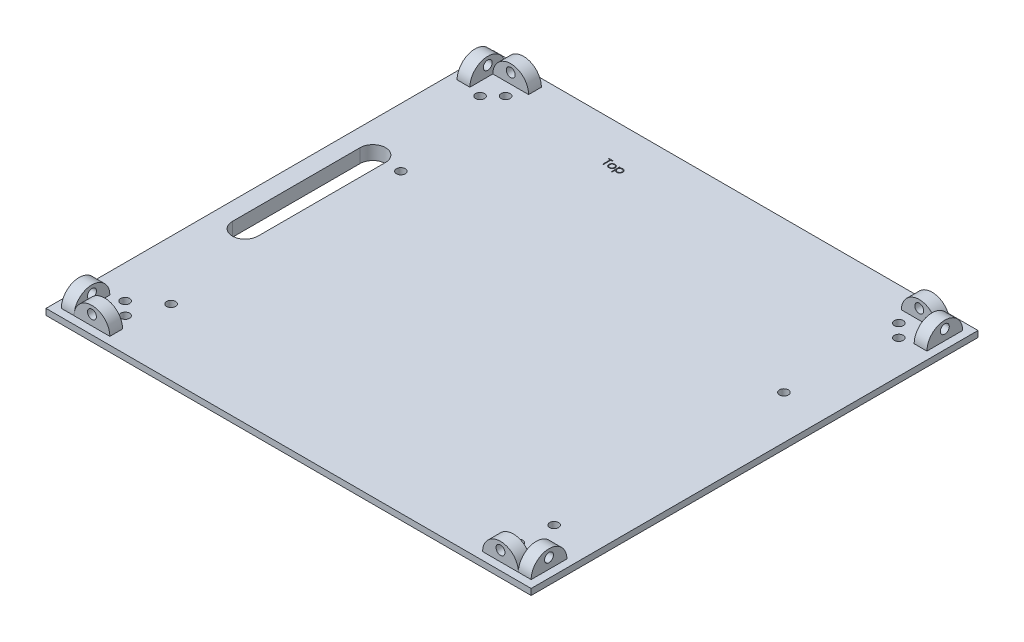
SolidWorks part; units mm, degrees
ref_plane "Front Plane" through (0, 0, 0) normal (0, 0, 1) x (1, 0, 0)
ref_plane "Top Plane" through (0, 0, 0) normal (0, 1, 0) x (1, 0, 0)
ref_plane "Right Plane" through (0, 0, 0) normal (1, 0, 0) x (0, 0, -1)
sketch "Sketch1" plane through (0, 0, 0) normal (0, 1, 0) x (1, 0, 0)
  line L1 (-123.0644, -58.8857) -> (36.9356, -58.8857) construction
  line L2 (-123.0644, -58.8857) -> (-123.0644, 34.1143) construction
  line L3 (-123.0644, 34.1143) -> (36.9356, 34.1143) construction
  line L4 (36.9356, -58.8857) -> (36.9356, 34.1143) construction
  line L5 (-143.0644, 90.1143) -> (40.9356, 90.1143) construction
  line L6 (40.9356, -78.8857) -> (40.9356, 90.1143) construction
  line L10 (-146.0644, 93.1143) -> (43.9356, 93.1143)
  line L11 (43.9356, -81.8857) -> (43.9356, 93.1143)
  line L12 (-146.0644, -81.8857) -> (43.9356, -81.8857)
  line L13 (-146.0644, -81.8857) -> (-146.0644, 93.1143)
  line L14 (-143.0644, -78.8857) -> (40.9356, -78.8857) construction
  line L15 (-143.0644, -78.8857) -> (-143.0644, 90.1143) construction
  line L17 (113.9356, 62.2405) -> (53.9356, 62.2405) construction
  line L18 (113.9356, 62.2405) -> (113.9356, 2.2405) construction
  line L19 (113.9356, 2.2405) -> (53.9356, 2.2405) construction
  line L20 (53.9356, 62.2405) -> (53.9356, 2.2405) construction
  line L21 (-51.0644, 90.1143) -> (-51.0644, -78.8857) construction
  line L22 (-143.0644, 5.6143) -> (40.9356, 5.6143) construction
  circle A0 centre (-123.0644, 34.1143) radius 1.75
  circle A1 centre (26.9356, 34.1143) radius 1.75
  circle A2 centre (26.9356, -55.8857) radius 1.75
  circle A3 centre (-123.0644, -55.8857) radius 1.75
  dimension "D6" = 3.5
  dimension "D2" = 160
  dimension "D4" = 200
  dimension "D5" = 20
  dimension "D9" = 175
  dimension "D10" = 190
  dimension "D11" = 60
  dimension "D12" = 20
  dimension "D13" = 150
  dimension "D3" = 3
  dimension "D14" = 90
  dimension "D7" = 2
  dimension "D8" = 2
extrude "Base" add sketch "Sketch1" against normal blind 5.4
ref_plane "Plane1" through (-143.0644, 0, 0) normal (1, 0, 0) x (0, 0, -1)
sketch "Sketch3" plane through (-143.0644, 0, 0) normal (1, 0, 0) x (0, 0, -1)
  line L1 (-78.8857, 0) -> (90.1143, 0) construction
  line L2 (90.1143, 0) -> (83.1143, 0) construction
  line L3 (76.1143, 0) -> (90.1143, 0)
  line L4 (-78.8857, 0) -> (-64.8857, 0)
  line L5 (-71.8857, 7) -> (-71.8857, 0) construction
  line L6 (83.1143, 7) -> (83.1143, 0) construction
  line L7 (-78.8857, 0) -> (90.1143, 0) construction
  arc A0 (90.1143, 0) -> (76.1143, 0) centre (83.1143, 0) ccw
  arc A1 (-64.8857, 0) -> (-78.8857, 0) centre (-71.8857, 0) ccw
  circle A2 centre (-71.8857, 4) radius 1.75
  circle A3 centre (83.1143, 4) radius 1.75
  point P18 (93.1143, 0)
  dimension "D1" = 14
  dimension "D2" = 3.5
  dimension "D4" = 3.5
  dimension "D3" = 3
  dimension "D5" = 4
  dimension "D6" = 14
extrude "Long_Side_connectors" add sketch "Sketch3" along normal blind 5
ref_plane "Plane2" through (0, 0, 78.8857) normal (0, 0, 1) x (1, 0, 0)
sketch "Sketch4" plane through (0, 0, 78.8857) normal (0, 0, 1) x (1, 0, 0)
  line L1 (-138.0644, 0) -> (-124.0644, 0)
  line L2 (-138.0644, 0) -> (-124.0644, 0)
  line L3 (-131.0644, 7) -> (-131.0644, 0) construction
  arc A0 (-124.0644, 0) -> (-138.0644, 0) centre (-131.0644, 0) ccw
  circle A1 centre (-131.0644, 4) radius 1.75
  dimension "D1" = 14
  dimension "D2" = 4
extrude "Short_side_connectors" add sketch "Sketch4" against normal blind 5 contours A0 L3 A1 L2 | L3 A0 L1 A1
ref_plane "Plane6" through (0, 0, -5.6143) normal (0, 0, 1) x (1, 0, 0)
mirror "Mirror1" about plane through (0, 0, -5.6143) normal (0, 0, 1) of "Short_side_connectors"
ref_plane "Plane5" through (-51.0644, 0, 0) normal (1, 0, 0) x (0, 0, -1)
mirror "Mirror3" about plane through (-51.0644, 0, 0) normal (1, 0, 0) of "Long_Side_connectors", "Mirror1", "Short_side_connectors"
sketch "Sketch6" plane through (0, 0, 0) normal (0, 1, 0) x (1, 0, 0)
  line L0 (36.9356, -58.8857) -> (36.9356, 34.1143) construction
  line L1 (46.9356, -62.7595) -> (126.9356, -62.7595)
  line L2 (46.9356, -62.7595) -> (46.9356, -12.7595)
  line L3 (46.9356, -12.7595) -> (126.9356, -12.7595)
  line L4 (126.9356, -62.7595) -> (126.9356, -12.7595)
  line L5 (46.9356, -62.7595) -> (126.9356, -12.7595) construction
  line L6 (46.9356, -12.7595) -> (126.9356, -62.7595) construction
  line L7 (113.9356, 2.2405) -> (53.9356, 2.2405) construction
  point P0 (86.9356, -37.7595)
  point P9 (83.9356, 2.2405)
  dimension "D1" = 50
  dimension "D2" = 80
  dimension "D3" = 10
  dimension "D4" = 15
extrude "Estop_relay" [suppressed] add sketch "Sketch6" along normal blind 2 contours L3 L4 L1 L2
sketch "Sketch8" [suppressed] plane through (0, 2, 0) normal (0, 1, 0) x (1, 0, 0)
  line L0 (38.9356, -37.7595) -> (118.9356, -37.7595) construction
  line L1 (38.9356, -62.7595) -> (38.9356, -12.7595) construction
  line L2 (118.9356, -62.7595) -> (118.9356, -12.7595) construction
  line L3 (38.9356, -37.7595) -> (43.9356, -37.7595) construction
  line L4 (78.9356, -12.7595) -> (78.9356, -62.7595) construction
  line L5 (38.9356, -12.7595) -> (118.9356, -12.7595) construction
  line L6 (38.9356, -62.7595) -> (118.9356, -62.7595) construction
  circle A0 centre (43.9356, -37.7595) radius 1.77
  circle A1 centre (113.9356, -37.7595) radius 1.77
  dimension "D2" = 3.54
  dimension "D1" = 5
extrude "Estop_bolts" [suppressed] cut sketch "Sketch8" against normal blind 5.3
sketch "Sketch9" plane through (0, 0, 0) normal (0, 1, 0) x (1, 0, 0)
  line L0 (-128.0644, 30.1143) -> (-128.0644, 5.1143) construction
  line L1 (-120.5644, 30.1143) -> (-120.5644, 5.1143)
  line L2 (-135.5644, 30.1143) -> (-135.5644, 5.1143)
  line L3 (-143.0644, 90.1143) -> (40.9356, 90.1143) construction
  line L4 (-143.0644, -78.8857) -> (-143.0644, 90.1143) construction
  arc A0 (-120.5644, 30.1143) -> (-135.5644, 30.1143) centre (-128.0644, 30.1143) ccw
  arc A1 (-135.5644, 5.1143) -> (-120.5644, 5.1143) centre (-128.0644, 5.1143) ccw
  point P2 (-128.0644, 17.6143)
  dimension "D1" = 25
  dimension "D2" = 15
  dimension "D3" = 60
  dimension "D4" = 15
extrude "Cut-Extrude4" [suppressed] cut sketch "Sketch9" against normal up to next contours A0 L2 A1 L1
sketch "Sketch10" [suppressed] plane through (0, 0, 0) normal (0, 1, 0) x (1, 0, 0)
  line L0 (-126.8751, 25.1928) -> (-127.2079, -70.1564) construction
  line L1 (-120.5644, 30.1143) -> (-120.5644, 5.1143) construction
  text T0 "Power"
  text T1 "  M-     M+    B-    B+    Bd   - Bd+  Bed_out+   -\r\n"
  dimension "D1" = 0.2
extrude "Text" [suppressed] cut sketch "Sketch10" against normal blind 1 and the other way through all
sketch "Sketch11" plane through (0, 0, 0) normal (0, 1, 0) x (1, 0, 0)
  line L0 (-138.0644, -73.8857) -> (-124.0644, -73.8857) construction
  line L1 (-133.0644, -68.8857) -> (-128.0644, -68.8857) construction
  line L2 (-133.0644, -68.8857) -> (-133.0644, -63.8857) construction
  line L3 (-133.0644, -63.8857) -> (-128.0644, -63.8857) construction
  line L4 (-128.0644, -68.8857) -> (-128.0644, -63.8857) construction
  line L5 (-138.0644, -73.8857) -> (-138.0644, -64.8857) construction
  line L6 (-138.0644, 85.1143) -> (-124.0644, 85.1143) construction
  line L7 (-133.0644, 80.1143) -> (-128.0644, 80.1143) construction
  line L8 (-133.0644, 80.1143) -> (-133.0644, 75.1143) construction
  line L9 (-133.0644, 75.1143) -> (-128.0644, 75.1143) construction
  line L10 (-128.0644, 80.1143) -> (-128.0644, 75.1143) construction
  line L11 (-138.0644, 76.1143) -> (-138.0644, 85.1143) construction
  line L12 (-51.0644, -85.25) -> (-51.0644, 85.25) construction
  circle A0 centre (-133.0644, -63.8857) radius 1.75
  circle A1 centre (-128.0644, -68.8857) radius 1.75
  circle A2 centre (-133.0644, 75.1143) radius 1.75
  circle A3 centre (-128.0644, 80.1143) radius 1.75
  circle A4 centre (30.9356, -63.8857) radius 1.75
  circle A5 centre (25.9356, -68.8857) radius 1.75
  circle A6 centre (30.9356, 75.1143) radius 1.75
  circle A7 centre (25.9356, 80.1143) radius 1.75
  dimension "D3" = 3.5
  dimension "D4" = 3.5
  dimension "D8" = 5
  dimension "D1" = 5
  dimension "D2" = 5
  dimension "D5" = 5
  dimension "D6" = 5
  dimension "4" = 5
  dimension "D7" = 5
  dimension "D9" = 5
extrude "Cut-Extrude6" cut sketch "Sketch11" along normal through all from surface at -5.4 starting at face at (-123.0644, -5.4, 57.6357)
chamfer "Chamfer2" distance 3 angle 45 4 edges at (43.9356, -5.4, -5.6143) (-51.0644, -5.4, -93.1143) (-146.0644, -5.4, -5.6143) (-51.0644, -5.4, 81.8857)
sketch "Sketch12" plane through (0, 0, 0) normal (0, 1, 0) x (1, 0, 0)
  line L0 (-86.7128, 76.045) -> (-50.3276, 76.045) construction
  text T0 "Top"
extrude "Cut-Extrude7" cut sketch "Sketch12" against normal blind 1
sketch "Sketch13" plane through (0, 0, 0) normal (0, 1, 0) x (1, 0, 0)
  line L0 (-134.0644, 34.1143) -> (-134.0644, -15.8857) construction
  line L1 (-146.0644, 93.1143) -> (-146.0644, -81.8857) construction
  line L2 (-134.0644, 34.1143) -> (-134.0644, -15.8857) construction
  line L3 (-129.0644, 34.1143) -> (-129.0644, -15.8857)
  line L4 (-139.0644, 34.1143) -> (-139.0644, -15.8857)
  arc A0 (-129.0644, 34.1143) -> (-139.0644, 34.1143) centre (-134.0644, 34.1143) ccw
  arc A1 (-139.0644, -15.8857) -> (-129.0644, -15.8857) centre (-134.0644, -15.8857) ccw
  circle A3 centre (-123.0644, 34.1143) radius 1.75 construction
  point P4 (-134.0644, 9.1143)
  dimension "D2" = 10
  dimension "D1" = 12
  dimension "D3" = 50
  dimension "D4" = 0
extrude "Cut-Extrude8" cut sketch "Sketch13" against normal through all
